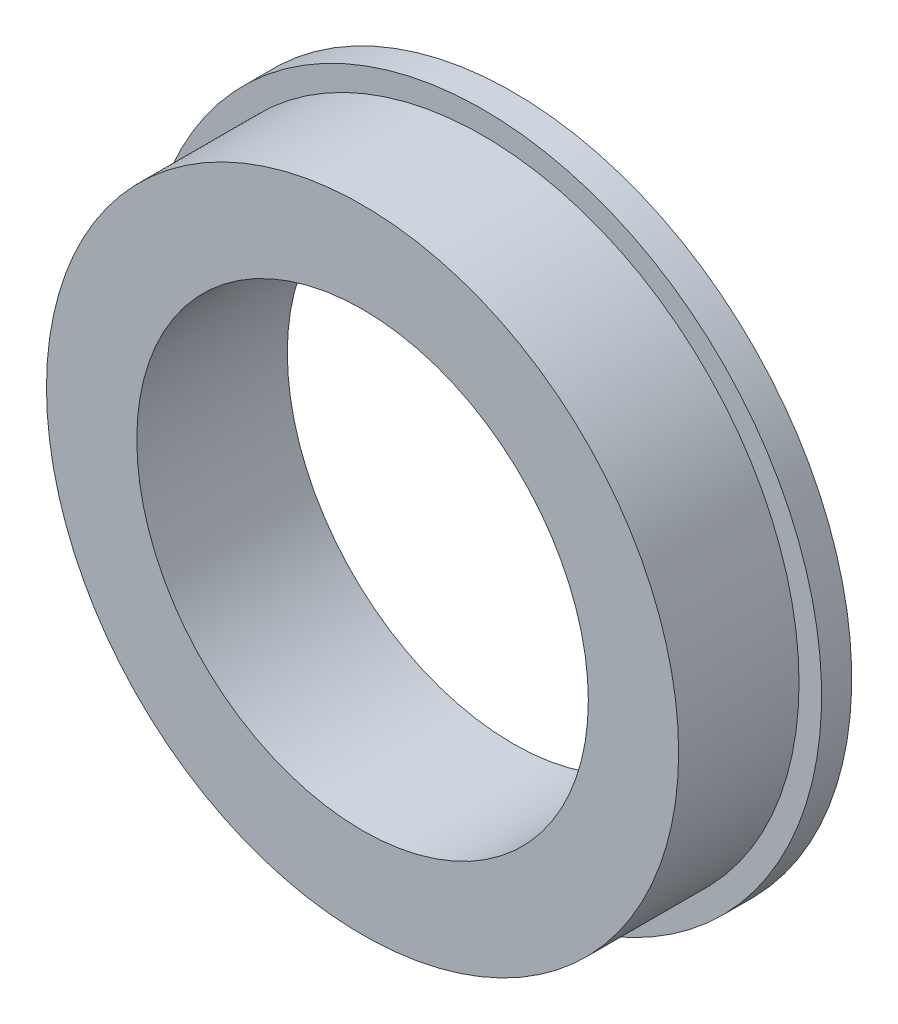
SolidWorks part; units mm, degrees
ref_plane "前视基准面" through (0, 0, 0) normal (0, 0, 1) x (1, 0, 0)
ref_plane "上视基准面" through (0, 0, 0) normal (0, 1, 0) x (1, 0, 0)
ref_plane "右视基准面" through (0, 0, 0) normal (1, 0, 0) x (0, 0, -1)
sketch "Sketch1" plane through (0, 0, 0) normal (0, 0, 1) x (1, 0, 0)
  circle A0 centre (0, 0) radius 22.5
  circle A1 centre (0, 0) radius 21
  circle A2 centre (0, 0) radius 15
  dimension "D1" = 45
  dimension "D2" = 42
  dimension "D3" = 30
extrude "Boss-Extrude1" add sketch "Sketch1" along normal blind 10 contours A1 A2
sketch "Sketch6" plane through (0, 0, 0) normal (0, 0, -1) x (-1, 0, 0)
  circle A0 centre (0, 0) radius 22.5
extrude "Boss-Extrude2" add sketch "Sketch6" against normal blind 2
sketch "Sketch7" plane through (0, 0, 10) normal (0, 0, 1) x (1, 0, 0)
  circle A0 centre (0, 0) radius 15
extrude "Cut-Extrude1" cut sketch "Sketch7" against normal through all
